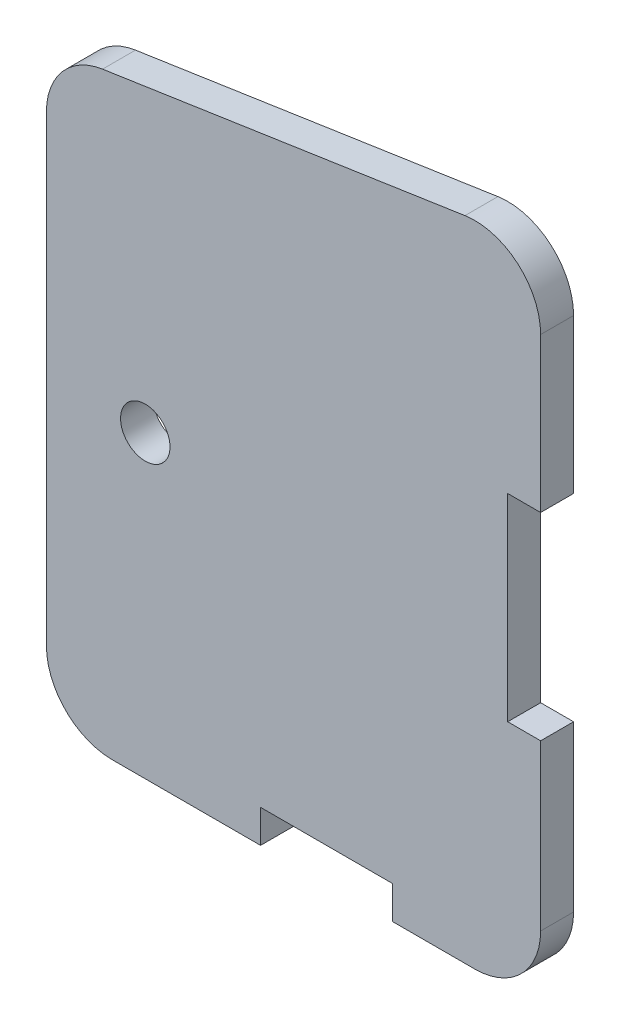
SolidWorks part; units mm, degrees
ref_plane "Front Plane" through (0, 0, 0) normal (0, 0, 1) x (1, 0, 0)
ref_plane "Top Plane" through (0, 0, 0) normal (0, 1, 0) x (1, 0, 0)
ref_plane "Right Plane" through (0, 0, 0) normal (1, 0, 0) x (0, 0, -1)
sketch "Sketch1" plane through (0, 0, 0) normal (0, 0, 1) x (1, 0, 0)
  line L0 (0, 56.1265) -> (0, 41.275)
  line L1 (-6.35, 0) -> (-14.2875, 0)
  line L4 (-38.1, 0) -> (-38.1, 57.785)
  line L13 (-47.625, 50.8877) -> (-47.625, 6.35)
  line L14 (-42.217, 57.1675) -> (-7.292, 62.4062)
  line L15 (0, 22.225) -> (0, 6.35)
  line L16 (-26.9875, 0) -> (-26.9875, 3.175)
  line L17 (-26.9875, 3.175) -> (-14.2875, 3.175)
  line L18 (-14.2875, 0) -> (-14.2875, 3.175)
  line L19 (0, 22.225) -> (-3.175, 22.225)
  line L21 (0, 41.275) -> (-3.175, 41.275)
  line L22 (-3.175, 22.225) -> (-3.175, 41.275)
  line L24 (-26.9875, 0) -> (-41.275, 0)
  circle A0 centre (-38.1, 28.8925) radius 2.3812
  arc A1 (0, 56.1265) -> (-7.292, 62.4062) centre (-6.35, 56.1265) ccw
  arc A2 (0, 6.35) -> (-6.35, 0) centre (-6.35, 6.35) cw
  arc A3 (-47.625, 6.35) -> (-41.275, 0) centre (-41.275, 6.35) ccw
  arc A4 (-47.625, 50.8877) -> (-42.217, 57.1675) centre (-41.275, 50.8877) cw
  point P7 (0, 63.5)
  point P11 (0, 0)
  dimension "D7" = 4.7625
  dimension "D3" = 6.35
  dimension "D2" = 63.5
  dimension "D4" = 38.1
  dimension "D6" = 9.525
  dimension "D8" = 3.175
  dimension "D9" = 19.05
  dimension "D10" = 3.175
  dimension "D11" = 12.7
  dimension "D12" = 22.225
  dimension "D13" = 14.2875
extrude "Boss-Extrude1" add sketch "Sketch1" along normal blind 3.175 contours A4 L13 A3 L24 L4 A0 L14 | A2 L15 L19 L22 L21 L0 A1 L14 L4 A0 L24 L16 L17 L18 L1
